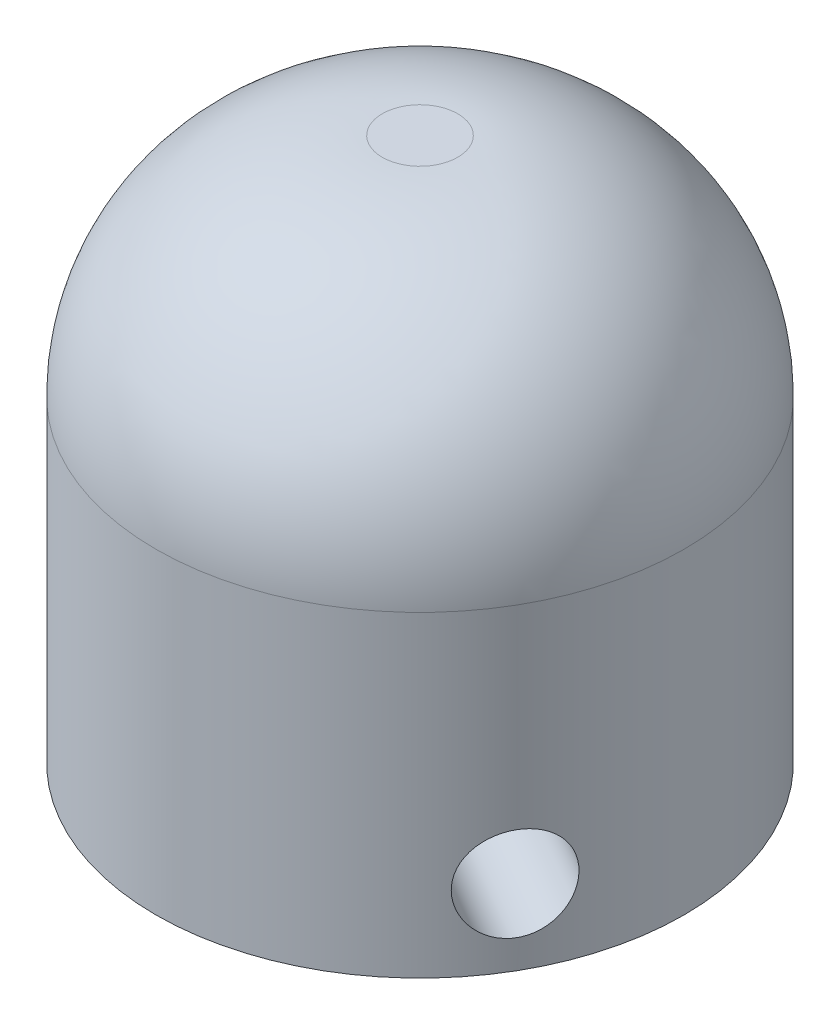
SolidWorks part; units mm, degrees
ref_plane "Face" through (0, 0, 0) normal (0, 0, 1) x (1, 0, 0)
ref_plane "Dessus" through (0, 0, 0) normal (0, 1, 0) x (1, 0, 0)
ref_plane "Droite" through (0, 0, 0) normal (1, 0, 0) x (0, 0, -1)
sketch "Esquisse1" plane through (0, 0, 0) normal (0, 0, 1) x (1, 0, 0)
  line L0 (0, 0) -> (0, 29.04) construction
  line L1 (7.5, 20) -> (0, 32.9904)
  line L2 (0, 35.9904) -> (0, 32.9904)
  line L5 (0, 35.9904) -> (17.5, 35.9904)
  line L6 (17.5, 35.9904) -> (17.5, 0)
  line L7 (17.5, 0) -> (7.5, 0)
  line L8 (7.5, 0) -> (7.5, 20)
  dimension "D1" = 20
  dimension "D2" = 3
  dimension "D3" = 30
  dimension "D4" = 10
  dimension "D5" = 15
revolve "Révolution1" add sketch "Esquisse1" angle 360 about L0
sketch "Esquisse2" plane through (0, 0, 0) normal (0, 0, 1) x (1, 0, 0)
  line L0 (0, 0) -> (0, 5) construction
  line L1 (-17.5, 0) -> (17.5, 0) construction
  circle A0 centre (0, 5) radius 3.1
  dimension "D1" = 6.2
  dimension "D2" = 5
extrude "Enlèv. mat.-Extru.1" cut sketch "Esquisse2" against normal blind 30 from offset 8 offset against normal yes
pattern_circular "Répétition circulaire1" count 3 over 360 about axis through (0, 0, 0) along (0, 1, 0) of "Enlèv. mat.-Extru.1"
fillet "Congé1" radius 15 1 edges at (0, 35.9904, -17.5)
